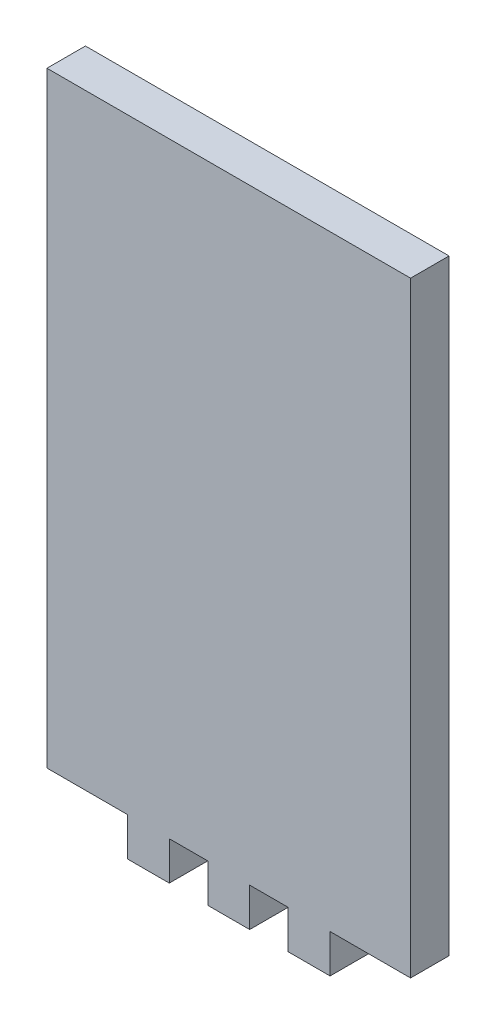
SolidWorks part; units mm, degrees
ref_plane "Front Plane" through (0, 0, 0) normal (0, 0, 1) x (1, 0, 0)
ref_plane "Top Plane" through (0, 0, 0) normal (0, 1, 0) x (1, 0, 0)
ref_plane "Right Plane" through (0, 0, 0) normal (1, 0, 0) x (0, 0, -1)
sketch "Sketch1" plane through (0, 0, 0) normal (0, 0, 1) x (1, 0, 0)
  line L0 (26.542, 0) -> (26.542, 6.35)
  line L2 (0, 6.35) -> (0, 106.36)
  line L3 (0, 106.36) -> (60, 106.36)
  line L4 (60, 6.35) -> (60, 106.36)
  line L7 (6.912, 6.35) -> (13.272, 6.35)
  line L8 (13.272, 0) -> (13.272, 6.35)
  line L9 (20.182, 6.35) -> (26.542, 6.35)
  line L10 (20.182, 0) -> (20.182, 6.35)
  line L11 (39.812, 0) -> (39.812, 6.35)
  line L12 (33.452, 6.35) -> (39.812, 6.35)
  line L13 (33.452, 0) -> (33.452, 6.35)
  line L15 (46.722, 6.35) -> (53.082, 6.35)
  line L16 (46.722, 0) -> (46.722, 6.35)
  line L17 (13.272, 0) -> (20.182, 0)
  line L18 (26.542, 0) -> (33.452, 0)
  line L19 (39.812, 0) -> (46.722, 0)
  line L21 (6.912, 6.35) -> (0, 6.35)
  line L22 (53.082, 6.35) -> (60, 6.35)
  line L24 (53.082, 0) -> (53.082, 6.35) [skipped]
  dimension "D2" = 60
  dimension "D3" = 6.36
  dimension "D5" = 4
extrude "Boss-Extrude1" add sketch "Sketch1" along normal blind 6.35
